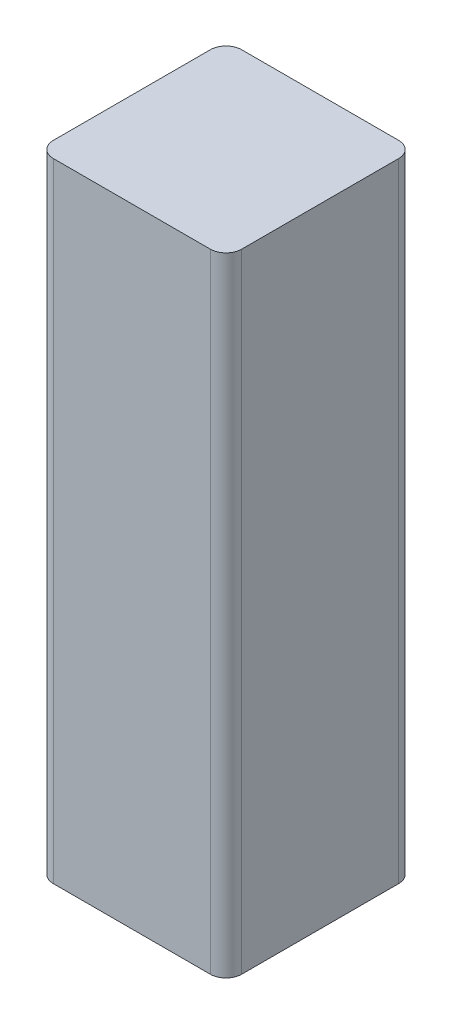
SolidWorks part; units mm, degrees
material "Plain Carbon Steel"
ref_plane "Front Plane" through (0, 0, 0) normal (0, 0, 1) x (1, 0, 0)
ref_plane "Top Plane" through (0, 0, 0) normal (0, 1, 0) x (1, 0, 0)
ref_plane "Right Plane" through (0, 0, 0) normal (1, 0, 0) x (0, 0, -1)
sketch "Sketch1" plane through (0, 0, 0) normal (0, 1, 0) x (1, 0, 0)
  line L1 (3, -3) -> (-3, -3)
  line L2 (3, -3) -> (3, 3)
  line L3 (3, 3) -> (-3, 3)
  line L4 (-3, -3) -> (-3, 3)
  line L5 (3, -3) -> (-3, 3) construction
  line L6 (3, 3) -> (-3, -3) construction
  point P0 (0, 0)
  dimension "D1" = 6
extrude "Boss-Extrude1" add sketch "Sketch1" along normal blind 20
fillet "Fillet1" radius 0.5 4 edges at (3, 10, -3) (-3, 10, -3) (-3, 10, 3) (3, 10, 3)
